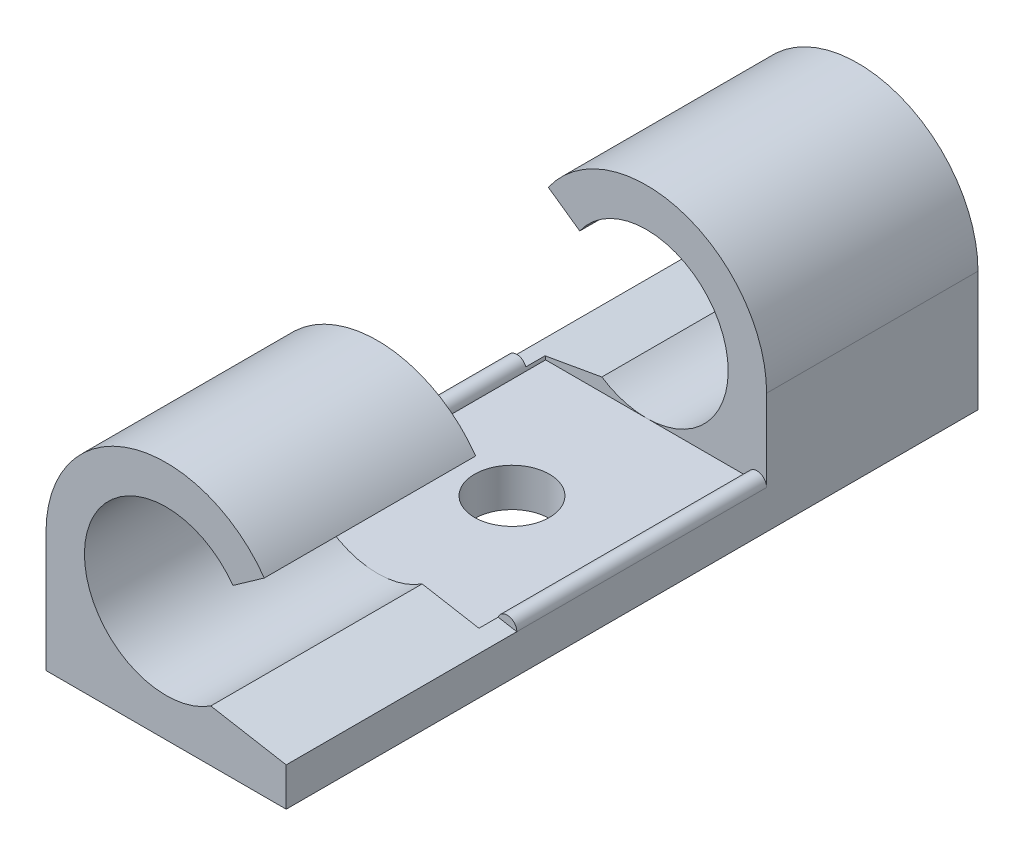
SolidWorks part; units mm, degrees
ref_plane "Plano frontal" through (0, 0, 0) normal (0, 0, 1) x (1, 0, 0)
ref_plane "Plano superior" through (0, 0, 0) normal (0, 1, 0) x (1, 0, 0)
ref_plane "Plano direito" through (0, 0, 0) normal (1, 0, 0) x (0, 0, -1)
sketch "Esboço1" plane through (0, 0, 0) normal (0, 0, 1) x (1, 0, 0)
  line L0 (-6.25, 0) -> (6.25, 0)
  line L1 (-6.25, 6.25) -> (6.25, 6.25)
  line L2 (-6.25, 6.25) -> (-6.25, -6.25)
  line L3 (-6.25, -6.25) -> (6.25, -6.25)
  line L4 (6.25, 6.25) -> (6.25, -6.25)
  line L5 (-6.25, 6.25) -> (6.25, -6.25) construction
  line L6 (-6.25, -6.25) -> (6.25, 6.25) construction
  circle A0 centre (0, 0) radius 6.25
  circle A2 centre (0, 0) radius 4.25
  point P0 (0, 0)
  point P12 (0, 0)
  dimension "D3" = 8.5
  dimension "D1" = 12.5
  dimension "D2" = 12.5
extrude "Ressalto-extrusão1" add sketch "Esboço1" along normal blind 11 contours A0 L2 L3 | A0 L3 L4 | A2 L0 A0 | A2 L0 A0
sketch "Esboço2" plane through (0, 0, 11) normal (0, 0, 1) x (1, 0, 0)
  line L0 (6.25, 0) -> (6.25, -6.25) construction
  line L1 (-6.25, -6.25) -> (6.25, -6.25)
  line L2 (-6.25, -6.25) -> (-6.25, -4.25)
  line L3 (-6.25, -4.25) -> (6.25, -4.25)
  line L4 (6.25, -6.25) -> (6.25, -4.25)
  line L5 (-6.25, -6.25) -> (6.25, -4.25) construction
  line L6 (-6.25, -4.25) -> (6.25, -6.25) construction
  circle A0 centre (0, 0) radius 4.25 construction
  point P4 (0, -5.25)
extrude "Ressalto-extrusão2" add sketch "Esboço2" along normal blind 7
sketch "Esboço3" plane through (0, 0, 18) normal (0, 0, 1) x (1, 0, 0)
  line L0 (6.25, -4.25) -> (0, -4.25) construction
  line L1 (6.25, -4.25) -> (0, -4.25) construction
  line L2 (0, 0) -> (0, -0.723) construction
  arc A0 (6.25, -4.25) -> (5.25, -4.25) centre (5.75, -4.25) ccw
  arc A1 (5.25, -4.25) -> (6.25, -4.25) centre (5.75, -4.25) ccw construction
  arc A2 (-6.25, -4.25) -> (-5.25, -4.25) centre (-5.75, -4.25) cw
  line M5 (6.25, -4.25) -> (-6.25, -4.25)
  dimension "D1" = 1
extrude "Ressalto-extrusão3" add sketch "Esboço3" against normal up to surface (7 mm away) contours A0 M5 | A2 M5 up to face at (0.7083, -1.0833, 11)
mirror "Espelhar1" about plane through (0, 0, 18) normal (0, 0, -1) of "Ressalto-extrusão2", "Ressalto-extrusão1", "Ressalto-extrusão3"
sketch "Esboço4" plane through (0, -4.25, 0) normal (0, 1, 0) x (1, 0, 0)
  line L0 (0, -11) -> (0, -18) construction
  line L2 (-5.25, -18) -> (5.25, -18) construction
  line L3 (-5.25, -11) -> (-5.25, -25) construction
  line L4 (5.25, -11) -> (5.25, -25) construction
  line L5 (-6.25, -11) -> (6.25, -11) construction
  circle A0 centre (0, -18) radius 1.95
  dimension "D1" = 3.9
extrude "Corte-extrusão1" cut sketch "Esboço4" against normal blind 2
sketch "Esboço5" plane through (0, 0, 36) normal (0, 0, 1) x (1, 0, 0)
  line L0 (6.25, -4.25) -> (0, -4.25) construction
  line L1 (6.25, 0) -> (6.25, -6.25) construction
  line L2 (-6.25, -6.25) -> (6.25, -6.25) construction
  line L3 (6, 1.75) -> (2.4841, 1.75) construction
  line L4 (2.4841, 1.75) -> (5.1094, 3.5995)
  line L5 (0, 0) -> (2.4841, 1.75) construction
  line L6 (6.25, -4.25) -> (2.3247, -3.5579)
  circle A0 centre (0, 0) radius 4.25 construction
  arc A1 (6.25, 0) -> (-6.25, 0) centre (0, 0) ccw construction
  circle M4 centre (0, 0) radius 4.25
  line M6 (6.25, -6.25) -> (6.25, 0)
  arc M7 (6.25, 0) -> (-6.25, 0) centre (0, 0) ccw
  dimension "D1" = 2
  dimension "D2" = 6
  dimension "D3" = 35.164
  dimension "D4" = 10
extrude "Corte-extrusão2" cut sketch "Esboço5" against normal blind 12 contours L4 L0 M4 M6 M7
sketch "Esboço6" plane through (0, 0, 0) normal (0, 0, -1) x (-1, 0, 0)
  line L0 (6.25, -4.25) -> (0, -4.25) construction
  line L1 (6.25, 0) -> (6.25, -6.25) construction
  line L2 (6.25, -6.25) -> (-6.25, -6.25) construction
  line L3 (5.7509, 2.4474) -> (3.4746, 2.4474) construction
  line L4 (6.25, -4.25) -> (2.3247, -3.5579)
  line L5 (3.4746, 2.4474) -> (5.4041, 3.8065)
  line L6 (0, 0) -> (3.4746, 2.4474) construction
  circle A0 centre (0, 0) radius 4.25 construction
  arc A1 (6.25, 0) -> (-6.25, 0) centre (0, 0) ccw construction
  circle M3 centre (0, 0) radius 4.25
  line M5 (6.25, -6.25) -> (6.25, 0)
  arc M6 (6.25, 0) -> (-6.25, 0) centre (0, 0) ccw
  dimension "D1" = 2
  dimension "D2" = 35.16
  dimension "D3" = 10
extrude "Corte-extrusão3" cut sketch "Esboço6" against normal blind 12 contours L5 L4 M3 M5 M6
equation "\"D2@Esboço1\"=\"D1@Esboço1\""
equation "\"D1@Esboço1\"=\"D3@Esboço1\"+4"
